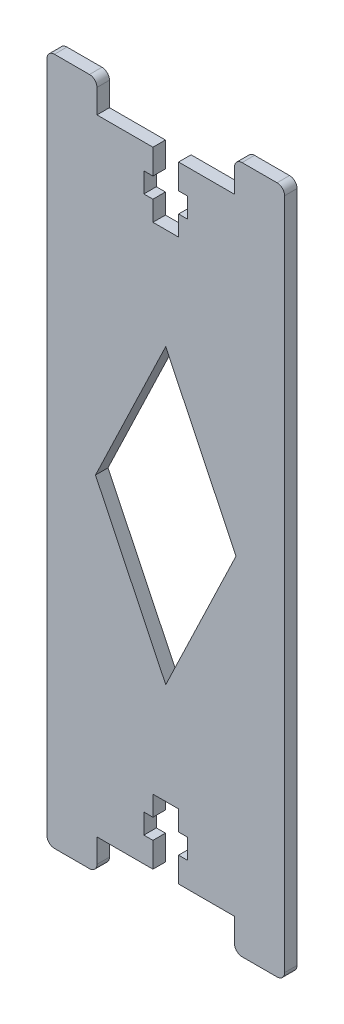
SolidWorks part; units mm, degrees
ref_plane "前视基准面" through (0, 0, 0) normal (0, 0, 1) x (1, 0, 0)
ref_plane "上视基准面" through (0, 0, 0) normal (0, 1, 0) x (1, 0, 0)
ref_plane "右视基准面" through (0, 0, 0) normal (1, 0, 0) x (0, 0, -1)
sketch "草图1" plane through (0, 0, 0) normal (0, 0, 1) x (1, 0, 0)
  line L0 (-3.9409, 0) -> (-3.9409, 9.9) construction
  line L1 (15.0591, 15.4) -> (15.0591, -94.6)
  line L2 (15.0591, -39.6) -> (-22.9409, -39.6) construction
  line L3 (-3.9409, -79.2) -> (-3.9409, -89.1) construction
  line L4 (7.0591, -94.6) -> (15.0591, -94.6)
  line L5 (7.0591, -89.6) -> (7.0591, -94.6)
  line L6 (-5.9909, 0) -> (-1.8909, 0)
  line L7 (-1.8909, 0) -> (-1.8909, 3.2)
  line L8 (-1.8909, 3.2) -> (-0.4409, 3.2)
  line L9 (-0.4409, 3.2) -> (-0.4409, 6.4)
  line L10 (-0.4409, 6.4) -> (-1.8909, 6.4)
  line L11 (-1.8909, 6.4) -> (-1.8909, 10.4)
  line L12 (-1.8909, 10.4) -> (7.0591, 10.4)
  line L13 (7.0591, 10.4) -> (7.0591, 15.4)
  line L14 (7.0591, 15.4) -> (15.0591, 15.4)
  line L15 (-1.8909, -89.6) -> (7.0591, -89.6)
  line L16 (-1.8909, -85.6) -> (-1.8909, -89.6)
  line L17 (-0.4409, -85.6) -> (-1.8909, -85.6)
  line L18 (-0.4409, -82.4) -> (-0.4409, -85.6)
  line L19 (-1.8909, -82.4) -> (-0.4409, -82.4)
  line L20 (-1.8909, -79.2) -> (-1.8909, -82.4)
  line L21 (-5.9909, -79.2) -> (-1.8909, -79.2)
  line L22 (-5.9909, -79.2) -> (-5.9909, -82.4)
  line L23 (-5.9909, -82.4) -> (-7.4409, -82.4)
  line L24 (-7.4409, -82.4) -> (-7.4409, -85.6)
  line L25 (-7.4409, -85.6) -> (-5.9909, -85.6)
  line L26 (-5.9909, -85.6) -> (-5.9909, -89.6)
  line L27 (-5.9909, -89.6) -> (-14.9409, -89.6)
  line L28 (-14.9409, 15.4) -> (-22.9409, 15.4)
  line L29 (-14.9409, 10.4) -> (-14.9409, 15.4)
  line L30 (-5.9909, 10.4) -> (-14.9409, 10.4)
  line L31 (-5.9909, 6.4) -> (-5.9909, 10.4)
  line L32 (-7.4409, 6.4) -> (-5.9909, 6.4)
  line L33 (-7.4409, 3.2) -> (-7.4409, 6.4)
  line L34 (-5.9909, 3.2) -> (-7.4409, 3.2)
  line L35 (-5.9909, 0) -> (-5.9909, 3.2)
  line L36 (-14.9409, -89.6) -> (-14.9409, -94.6)
  line L37 (-14.9409, -94.6) -> (-22.9409, -94.6)
  line L38 (-22.9409, 15.4) -> (-22.9409, -94.6)
  line L39 (-3.9409, 0) -> (-22.9409, -39.6) construction
  line L40 (-22.9409, -39.6) -> (-3.9409, -79.2) construction
  line L41 (-3.9409, -79.2) -> (15.0591, -39.6) construction
  line L42 (15.0591, -39.6) -> (-3.9409, 0) construction
  line L43 (-3.9409, -16.1819) -> (-15.1769, -39.6)
  line L44 (-15.1769, -39.6) -> (-3.9409, -63.0181)
  line L45 (-3.9409, -63.0181) -> (7.2951, -39.6)
  line L46 (7.2951, -39.6) -> (-3.9409, -16.1819)
  line L47 (11.0591, 15.4) -> (11.0591, 9.7) construction
  point P26 (-3.9409, -39.6)
  point P50 (-0.4409, 4.8)
  dimension "D1" = 2.05
  dimension "D2" = 3.2
  dimension "D3" = 7
  dimension "D4" = 3.2
  dimension "D5" = 4
  dimension "D6" = 15
  dimension "D7" = 5
  dimension "D8" = 8
  dimension "D9" = 110
  dimension "D10" = 7
extrude "凸台-拉伸1" add sketch "草图1" along normal blind 2
fillet "圆角1" radius 1.2 8 edges at (-22.9409, 15.4, 1) (-14.9409, 15.4, 1) (7.0591, 15.4, 1) (15.0591, 15.4, 1) (-22.9409, -94.6, 1) (-14.9409, -94.6, 1) (7.0591, -94.6, 1) (15.0591, -94.6, 1)
sketch "草图2" plane through (0, 10.4, 0) normal (0, 1, 0) x (1, 0, 0)
  line L0 (-5.9909, -1) -> (-1.8909, -1)
  line L1 (-5.9909, -2) -> (-5.9909, 0) construction
  line L2 (-1.8909, -2) -> (-1.8909, 0) construction
  circle A0 centre (-3.9409, -1) radius 2.05
sketch "草图3" plane through (0, -89.6, 0) normal (0, -1, 0) x (1, 0, 0)
  line L0 (-5.9909, 1) -> (-1.8909, 1)
  line L1 (-5.9909, 2) -> (-5.9909, 0) construction
  line L2 (-1.8909, 2) -> (-1.8909, 0) construction
  circle A0 centre (-3.9409, 1) radius 2.05
